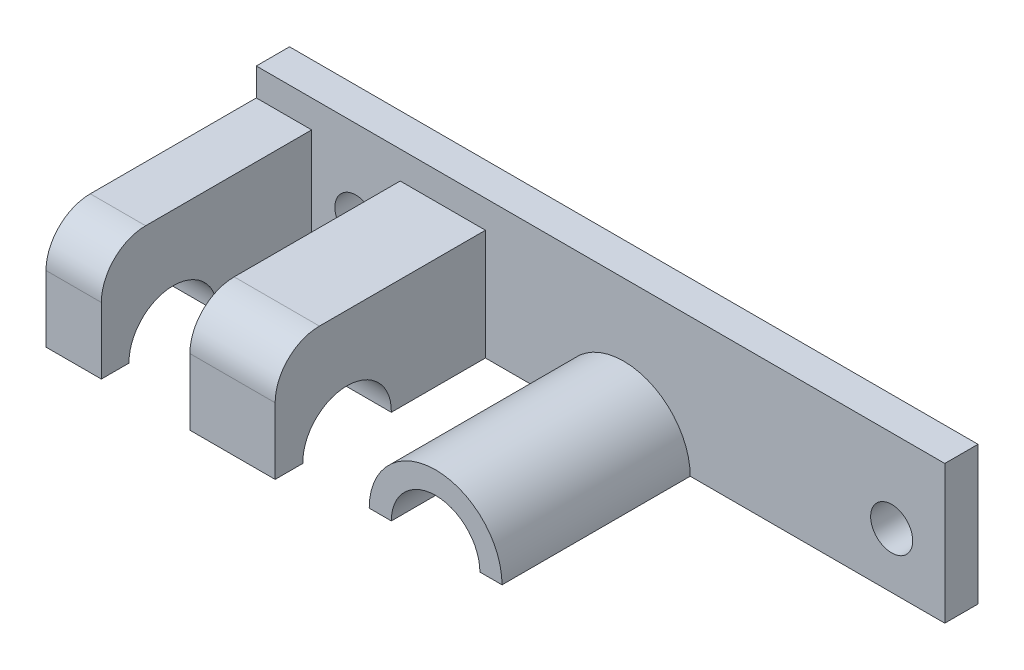
SolidWorks part; units mm, degrees
ref_plane "Front Plane" through (0, 0, 0) normal (0, 0, 1) x (1, 0, 0)
ref_plane "Top Plane" through (0, 0, 0) normal (0, 1, 0) x (1, 0, 0)
ref_plane "Right Plane" through (0, 0, 0) normal (1, 0, 0) x (0, 0, -1)
sketch "Sketch1" plane through (0, 0, 0) normal (0, 0, 1) x (1, 0, 0)
  line L0 (-35.6557, 0) -> (35.5199, 0) construction
  line L1 (-29, 12.5) -> (29, 12.5)
  line L2 (-29, 12.5) -> (-29, -12.5)
  line L3 (-29, -12.5) -> (29, -12.5)
  line L4 (29, 12.5) -> (29, -12.5)
  line L5 (-29, 12.5) -> (29, -12.5) construction
  line L6 (-29, -12.5) -> (29, 12.5) construction
  line L7 (0, 14.8056) -> (0, -17.7939) construction
  circle A0 centre (24.2, 5) radius 1.9
  circle A1 centre (24.2, -5) radius 1.9
  circle A2 centre (-24.2, 5) radius 1.9
  circle A3 centre (-24.2, -5) radius 1.9
  point P0 (0, 0)
  dimension "D3" = 3.8
  dimension "D4" = 3.8
  dimension "D7" = 3.8
  dimension "D8" = 3.8
  dimension "D1" = 58
  dimension "D2" = 25
  dimension "D5" = 10
  dimension "D6" = 5
  dimension "D10" = 24.2
extrude "Boss-Extrude1" add sketch "Sketch1" along normal blind 3
sketch "Sketch2" plane through (0, 0, 0) normal (0, 0, 1) x (1, 0, 0)
  line L0 (-31.697, 0) -> (34.595, 0) construction
  line L1 (0, 15.9391) -> (0, -16.084) construction
  circle A0 centre (0, 0) radius 6
  dimension "D1" = 12
extrude "Boss-Extrude2" add sketch "Sketch2" along normal blind 20
sketch "Sketch3" plane through (0, 0, 20) normal (0, 0, 1) x (1, 0, 0)
  line L0 (0, 15.1421) -> (0, -15.287) construction
  line L1 (-31.4072, 0) -> (31.8419, 0) construction
  circle A0 centre (0, 0) radius 4
  dimension "D1" = 8
extrude "Cut-Extrude1" cut sketch "Sketch3" against normal through all
sketch "Sketch4" plane through (0, 0, 3) normal (0, 0, 1) x (1, 0, 0)
  line L0 (-32.2766, 0) -> (-1.7026, 0) construction
  line L1 (0, 15.8445) -> (0, -16.1506) construction
  line L2 (-20.2, 9.9981) -> (-12.5, 9.9981)
  line L3 (-20.2, 9.9981) -> (-20.2, -9.9981)
  line L4 (-20.2, -9.9981) -> (-12.5, -9.9981)
  line L5 (-12.5, 9.9981) -> (-12.5, -9.9981)
  line L6 (-20.2, 9.9981) -> (-12.5, -9.9981) construction
  line L7 (-20.2, -9.9981) -> (-12.5, 9.9981) construction
  point P3 (-16.35, 0)
  dimension "D1" = 12.5
extrude "Boss-Extrude3" add sketch "Sketch4" along normal blind 19
sketch "Sketch5" plane through (-20.2, 0, 0) normal (-1, 0, 0) x (0, 0, 1)
  line L0 (-1.6546, 0) -> (24.695, 0) construction
  line L1 (15.5, 11.5987) -> (15.5, -11.437) construction
  line L2 (3, 9.9981) -> (3, -9.9981) construction
  circle A0 centre (15.5, 0.0808) radius 4
  dimension "D1" = 8
  dimension "D2" = 12.5
extrude "Cut-Extrude2" cut sketch "Sketch5" against normal up to next
fillet "Fillet1" radius 4 2 edges at (-16.35, -9.9981, 22) (-16.35, 9.9981, 22)
sketch "Sketch7" plane through (0, 0, 3) normal (0, 0, 1) x (1, 0, 0)
  line L0 (-29, -12.5) -> (29, -12.5) construction
  line L1 (-29, 12.5) -> (-33.2, 12.5)
  line L2 (-29, 12.5) -> (-29, -12.5)
  line L3 (-29, -12.5) -> (-33.2, -12.5)
  line L4 (-33.2, 12.5) -> (-33.2, -12.5)
  line L6 (-20.2, 5.9981) -> (-20.2, -5.9981) construction
  dimension "D1" = 13
extrude "Boss-Extrude4" add sketch "Sketch7" against normal blind 3
sketch "Sketch8" plane through (0, 0, 3) normal (0, 0, 1) x (1, 0, 0)
  line L1 (-28.2, 9.9981) -> (-33.2, 9.9981)
  line L2 (-28.2, 9.9981) -> (-28.2, -9.9981)
  line L3 (-28.2, -9.9981) -> (-33.2, -9.9981)
  line L4 (-33.2, 9.9981) -> (-33.2, -9.9981)
  line L5 (-20.2, -9.9981) -> (-12.5, -9.9981) construction
  line L7 (-12.5, 9.9981) -> (-20.2, 9.9981) construction
  dimension "D2" = 5
extrude "Boss-Extrude5" add sketch "Sketch8" along normal blind 19
sketch "Sketch9" plane through (-28.2, 0, 0) normal (1, 0, 0) x (0, 0, -1)
  line L0 (-20.1823, 0) -> (-11.5543, 0) construction
  line L1 (-15.5, 4.3115) -> (-15.5, -4.1843) construction
  circle A0 centre (-15.5, 0.0636) radius 4
  dimension "D1" = 8
extrude "Cut-Extrude3" cut sketch "Sketch9" against normal up to next
fillet "Fillet2" radius 4 2 edges at (-30.7, -9.9981, 22) (-30.7, 9.9981, 22)
sketch "Sketch10" plane through (0, 0, 0) normal (0, 0, -1) x (-1, 0, 0)
  line L0 (-30.3511, 0) -> (37.4351, 0) construction
  line L1 (-29, -12.5) -> (33.2, -12.5)
  line L2 (-29, -12.5) -> (-29, 0)
  line L3 (-29, 0) -> (33.2, 0)
  line L4 (33.2, -12.5) -> (33.2, 0)
  line L5 (33.2, 12.5) -> (33.2, -12.5) construction
extrude "Cut-Extrude4" cut sketch "Sketch10" against normal through all
